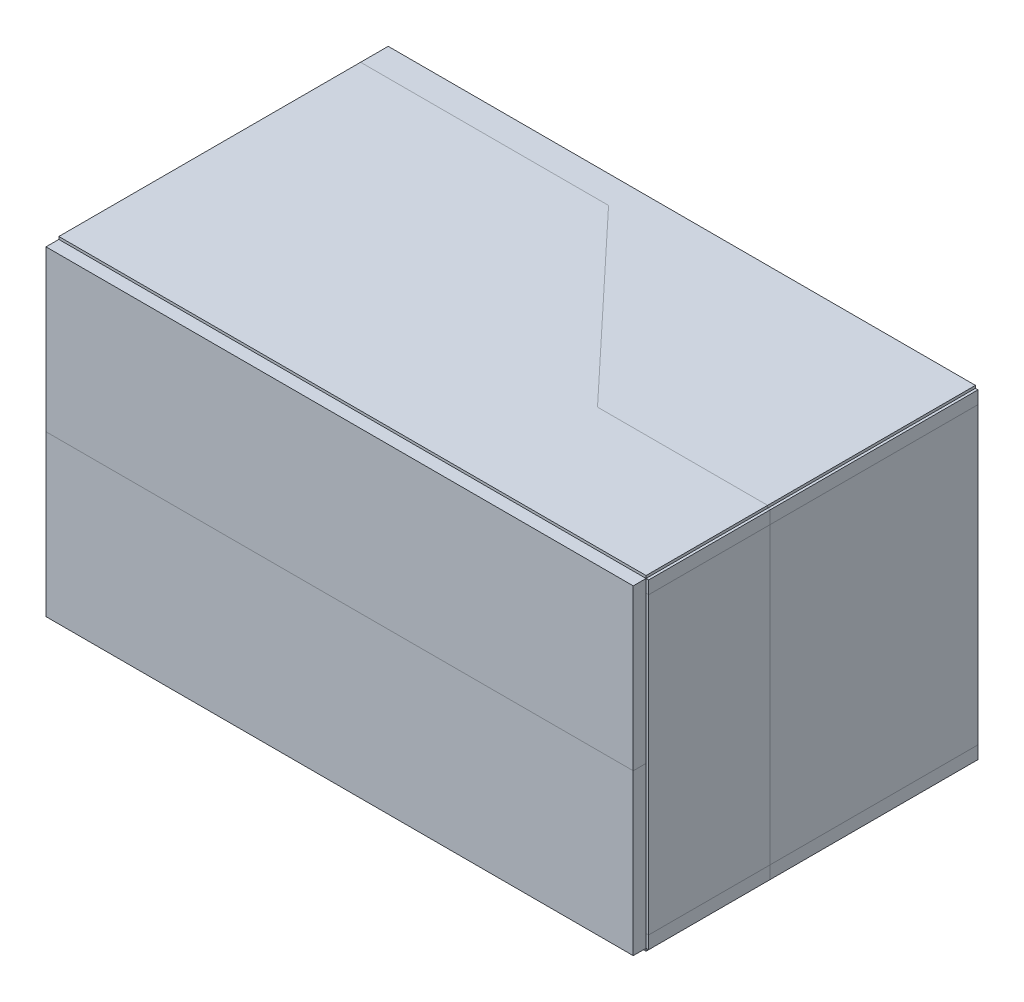
SolidWorks part; units mm, degrees
other "바닥"
other "우측면"
other "정면"
other "좌측면"
other "천장1"
other "천장2"
other "후면"
other "하단인테리어1"
other "상단인테리어1"
other "후면상단작음1"
other "후면하단작음1"
other "후면상단큼1"
other "후면하단큼1"
other "하단인테리어2"
other "상단인테리어2"
other "후면상단작음2"
other "후면하단작음2"
other "세탁건조기1"
other "세탁건조기다이얼1"
other "의자2"
other "의자1"
other "테이블"
other "TV"
other "에어컨"
ref_plane "정면" through (0, 0, 0) normal (0, 0, 1) x (1, 0, 0)
ref_plane "윗면" through (0, 0, 0) normal (0, 1, 0) x (1, 0, 0)
ref_plane "우측면" through (0, 0, 0) normal (1, 0, 0) x (0, 0, -1)
sketch "스케치1" plane through (0, 0, 0) normal (0, 0, 1) x (1, 0, 0)
  line L1 (51, 74.896) -> (280, 74.896)
  line L2 (51, 74.896) -> (51, -50)
  line L3 (51, -50) -> (280, -50)
  line L4 (280, 74.896) -> (280, -50)
extrude "보스-돌출1" add sketch "스케치1" along normal up to surface (7.8606 mm away)
sketch "스케치2" plane through (0, 0, 7.8606) normal (0, 0, 1) x (1, 0, 0)
  line L0 (280, 74.896) -> (280, -50) construction
  line L1 (51, 74.896) -> (280, 74.896)
  line L2 (51, 74.896) -> (51, 69.896)
  line L3 (51, 69.896) -> (280, 69.896)
  line L4 (280, 74.896) -> (280, 69.896)
  dimension "D1" = 5
extrude "컷-돌출1" cut sketch "스케치2" against normal up to surface (7.8606 mm away) contours L1 L3 L2 up to face at (165.5, 12.448, 0)
sketch "스케치4" plane through (0, 0, 7.8606) normal (0, 0, 1) x (1, 0, 0)
  line L0 (280, 69.896) -> (280, -50) construction
  line L1 (51, -50) -> (280, -50)
  line L2 (51, -50) -> (51, -45)
  line L3 (51, -45) -> (280, -45)
  line L4 (280, -50) -> (280, -45)
  line M1 (280, -50) -> (280, 69.896)
  line M3 (51, 69.896) -> (51, -50)
  line M4 (51, -50) -> (280, -50)
  dimension "D1" = 5
extrude "컷-돌출2" cut sketch "스케치4" against normal up to surface (7.8606 mm away) contours L3 M3 M4 M1 up to face at (165.5, 9.948, 0)
sketch "스케치5" plane through (0, 0, 7.8606) normal (0, 0, 1) x (1, 0, 0)
  line L0 (51, -45) -> (280, -45) construction
  line L1 (280, 69.896) -> (275, 69.896)
  line L2 (280, 69.896) -> (280, -45)
  line L3 (280, -45) -> (275, -45)
  line L4 (275, 69.896) -> (275, -45)
  line M1 (51, -45) -> (280, -45)
  line M2 (280, -45) -> (280, 69.896)
  line M3 (280, 69.896) -> (51, 69.896)
  dimension "D1" = 5
extrude "컷-돌출3" cut sketch "스케치5" against normal up to surface (7.8606 mm away) contours L4 M3 M1 M2 up to face at (165.5, 12.448, 0)
sketch "스케치6" plane through (0, 69.896, 0) normal (0, 1, 0) x (1, 0, 0)
  line L1 (51, 0) -> (280, 0)
  line L2 (51, 0) -> (51, -128.4421)
  line L3 (51, -128.4421) -> (280, -128.4421)
  line L4 (280, 0) -> (280, -128.4421)
extrude "보스-돌출3" add sketch "스케치6" along normal blind 5 separate body
sketch "스케치7" plane through (0, 0, 7.8606) normal (0, 0, 1) x (1, 0, 0)
  line L0 (51, -45) -> (275, -45) construction
  line L1 (51, 69.896) -> (56, 69.896)
  line L2 (51, 69.896) -> (51, -45)
  line L3 (51, -45) -> (56, -45)
  line L4 (56, 69.896) -> (56, -45)
  dimension "D1" = 5
extrude "보스-돌출4" add sketch "스케치7" along normal up to surface (120.5815 mm away) separate body up to face at (165.5, 72.396, 128.4421)
sketch "스케치8" plane through (0, -45, 0) normal (0, -1, 0) x (1, 0, 0)
  line L1 (51, 128.4421) -> (280, 128.4421)
  line L2 (51, 128.4421) -> (51, 0)
  line L3 (51, 0) -> (280, 0)
  line L4 (280, 128.4421) -> (280, 0)
extrude "보스-돌출5" add sketch "스케치8" along normal blind 5 separate body
sketch "스케치9" plane through (0, 0, 128.4421) normal (0, 0, 1) x (1, 0, 0)
  line L1 (51, 74.896) -> (280, 74.896)
  line L2 (51, 74.896) -> (51, 12.446)
  line L3 (51, 12.446) -> (280, 12.446)
  line L4 (280, 74.896) -> (280, 12.446)
  dimension "D1" = 62.45
extrude "보스-돌출6" add sketch "스케치9" along normal blind 5 separate body
sketch "스케치10" plane through (0, 0, 128.4421) normal (0, 0, 1) x (1, 0, 0)
  line L1 (51, 12.446) -> (280, 12.446)
  line L2 (51, 12.446) -> (51, -50)
  line L3 (51, -50) -> (280, -50)
  line L4 (280, 12.446) -> (280, -50)
extrude "보스-돌출7" add sketch "스케치10" along normal blind 5 separate body
sketch "스케치11" plane through (275, 0, 0) normal (1, 0, 0) x (0, 0, -1)
  line L1 (0, -45) -> (-128.4421, -45)
  line L2 (0, -45) -> (0, 69.896)
  line L3 (0, 69.896) -> (-128.4421, 69.896)
  line L4 (-128.4421, -45) -> (-128.4421, 69.896)
extrude "보스-돌출8" add sketch "스케치11" along normal blind 5 separate body
sketch "스케치12" plane through (0, -50, 0) normal (0, -1, 0) x (1, 0, 0)
  line L0 (51, 10.7712) -> (147.7059, 10.7712)
  line L1 (51, 128.4421) -> (51, 0) construction
  line L2 (147.7059, 10.7712) -> (213.6585, 81.0356)
  line L3 (213.6585, 81.0356) -> (280, 81.0356)
  line L4 (280, 0) -> (280, 128.4421) construction
  line L5 (51, 10.7712) -> (51, 0)
  line L6 (51, 0) -> (280, 0)
  line L7 (280, 0) -> (280, 81.0356)
extrude "보스-돌출9" add sketch "스케치12" along normal blind 1 separate body
sketch "스케치13" plane through (0, -50, 0) normal (0, -1, 0) x (1, 0, 0)
  line L0 (51, 128.4421) -> (51, 10.7712)
  line L1 (51, 10.7712) -> (147.7059, 10.7712)
  line L2 (147.7059, 10.7712) -> (213.6585, 81.0356)
  line L3 (213.6585, 81.0356) -> (280, 81.0356)
  line L4 (280, 81.0356) -> (280, 128.4421)
  line L5 (280, 128.4421) -> (51, 128.4421)
extrude "보스-돌출10" add sketch "스케치13" along normal blind 1 separate body
sketch "스케치14" plane through (280, 0, 0) normal (1, 0, 0) x (0, 0, -1)
  line L1 (-81.0356, -50) -> (-128.4421, -50)
  line L2 (-81.0356, -50) -> (-81.0356, -45)
  line L3 (-81.0356, -45) -> (-128.4421, -45)
  line L4 (-128.4421, -50) -> (-128.4421, -45)
extrude "보스-돌출11" add sketch "스케치14" along normal blind 1 separate body
sketch "스케치15" plane through (280, 0, 0) normal (1, 0, 0) x (0, 0, -1)
  line L1 (-81.0356, -50) -> (0, -50)
  line L2 (-81.0356, -50) -> (-81.0356, -45)
  line L3 (-81.0356, -45) -> (0, -45)
  line L4 (0, -50) -> (0, -45)
extrude "보스-돌출12" add sketch "스케치15" along normal blind 1 separate body
sketch "스케치16" plane through (280, 0, 0) normal (1, 0, 0) x (0, 0, -1)
  line L0 (-128.4421, 69.896) -> (0, 69.896) construction
  line L1 (-128.4421, -45) -> (-81.0356, -45)
  line L2 (-128.4421, -45) -> (-128.4421, 69.896)
  line L3 (-128.4421, 69.896) -> (-81.0356, 69.896)
  line L4 (-81.0356, -45) -> (-81.0356, 69.896)
extrude "보스-돌출13" add sketch "스케치16" along normal blind 1 separate body
sketch "스케치17" plane through (280, 0, 0) normal (1, 0, 0) x (0, 0, -1)
  line L0 (0, 74.896) -> (0, 69.896) construction
  line L1 (-81.0356, -45) -> (0, -45)
  line L2 (-81.0356, -45) -> (-81.0356, 69.896)
  line L3 (-81.0356, 69.896) -> (0, 69.896)
  line L4 (0, -45) -> (0, 69.896)
  line L5 (-128.4421, 69.896) -> (0, 69.896) construction
extrude "보스-돌출14" add sketch "스케치17" along normal blind 1 separate body
ref_plane "평면1" through (0, 12.446, 0) normal (0, 1, 0) x (1, 0, 0)
mirror "대칭 복사2" about plane through (0, 12.446, 0) normal (0, 1, 0) of bodies 112 113 114 115
other "바디 저장1"
other "바디 저장2"
sketch "스케치18" plane through (0, 0, 7.8606) normal (0, 0, 1) x (1, 0, 0)
  line L1 (56, 69.896) -> (110.75, 69.896)
  line L2 (56, 69.896) -> (56, 29.896)
  line L3 (56, 29.896) -> (110.75, 29.896)
  line L4 (110.75, 69.896) -> (110.75, 29.896)
  dimension "D1" = 54.75
  dimension "D2" = 40
extrude "보스-돌출15" add sketch "스케치18" along normal blind 60.29 separate body
sketch "스케치20" plane through (0, 29.896, 0) normal (0, -1, 0) x (1, 0, 0)
  line L0 (83.375, 68.1506) -> (83.375, 7.8606) construction
  line L1 (56, 68.1506) -> (110.75, 68.1506) construction
  line L2 (56, 7.8606) -> (110.75, 7.8606) construction
  circle A0 centre (83.375, 30.1418) radius 20
  dimension "D1" = 40
extrude "보스-돌출16" add sketch "스케치20" along normal blind 3
sketch "스케치21" plane through (0, 26.896, 0) normal (0, -1, 0) x (1, 0, 0)
  circle A0 centre (83.375, 30.1418) radius 16
  circle A1 centre (83.375, 30.1418) radius 20
  circle A2 centre (83.375, 30.1418) radius 20
  dimension "D1" = 0
  dimension "D2" = 4
extrude "컷-돌출4" cut sketch "스케치21" against normal blind 1 contours A0
sketch "스케치22" plane through (0, 29.896, 0) normal (0, -1, 0) x (1, 0, 0)
  line L0 (83.375, 68.1506) -> (83.375, 7.8606) construction
  line L1 (56, 68.1506) -> (110.75, 68.1506) construction
  line L2 (56, 7.8606) -> (110.75, 7.8606) construction
  circle A0 centre (83.375, 61.1506) radius 3.5
  dimension "D1" = 7
  dimension "D2" = 7
extrude "보스-돌출17" add sketch "스케치22" along normal blind 1 separate body
sketch "스케치23" plane through (0, 29.896, 0) normal (0, -1, 0) x (1, 0, 0)
  line L0 (63.0828, 65.5864) -> (73.9386, 65.5864)
  line L1 (64.0828, 64.5864) -> (72.9386, 64.5864)
  line L2 (61.0828, 61.5864) -> (61.0828, 59.5273)
  line L3 (64.0828, 56.5273) -> (72.9386, 56.5273)
  line L4 (75.9386, 61.5864) -> (75.9386, 59.5273)
  line L5 (76.9386, 62.5864) -> (76.9386, 59.5273)
  line L6 (64.0828, 55.5273) -> (72.9386, 55.5273)
  line L7 (60.0828, 62.5864) -> (60.0828, 59.5273)
  line L8 (60.0828, 65.5864) -> (76.9386, 65.5864) construction
  line L9 (60.0828, 65.5864) -> (60.0828, 59.5273) construction
  line L10 (76.9386, 65.5864) -> (76.9386, 59.5273) construction
  line L11 (61.0828, 64.5864) -> (75.9386, 64.5864) construction
  line L12 (61.0828, 64.5864) -> (61.0828, 59.5273) construction
  line L13 (75.9386, 64.5864) -> (75.9386, 59.5273) construction
  arc A0 (64.0828, 56.5273) -> (61.0828, 59.5273) centre (64.0828, 59.5273) cw
  arc A1 (75.9386, 59.5273) -> (72.9386, 56.5273) centre (72.9386, 59.5273) cw
  arc A2 (76.9386, 59.5273) -> (72.9386, 55.5273) centre (72.9386, 59.5273) cw
  arc A3 (64.0828, 55.5273) -> (60.0828, 59.5273) centre (64.0828, 59.5273) cw
  arc A4 (63.0828, 65.5864) -> (60.0828, 62.5864) centre (63.0828, 62.5864) ccw
  arc A5 (76.9386, 62.5864) -> (73.9386, 65.5864) centre (73.9386, 62.5864) ccw
  arc A6 (64.0828, 64.5864) -> (61.0828, 61.5864) centre (64.0828, 61.5864) ccw
  arc A7 (75.9386, 61.5864) -> (72.9386, 64.5864) centre (72.9386, 61.5864) ccw
  dimension "D1" = 3
  dimension "D2" = 3
  dimension "D4" = 3
  dimension "D5" = 3
  dimension "D6" = 3
  dimension "D7" = 3
  dimension "D3" = 1
extrude "컷-돌출5" cut sketch "스케치23" against normal blind 1
sketch "스케치24" plane through (0, 29.896, 0) normal (0, -1, 0) x (1, 0, 0)
  line L1 (91.1649, 65.5864) -> (107.3673, 65.5864)
  line L2 (91.1649, 65.5864) -> (91.1649, 56.4231)
  line L3 (91.1649, 56.4231) -> (107.3673, 56.4231)
  line L4 (107.3673, 65.5864) -> (107.3673, 56.4231)
extrude "컷-돌출6" cut sketch "스케치24" against normal blind 1
pattern_linear "선형 패턴1" count 4 spacing 54.75 along (1, 0, 0) of bodies 161 163
mirror "대칭 복사3" about plane through (0, 0, 68.1506) normal (0, 0, 1) of bodies 163 161 167 164 168 165 169 166
sketch "스케치25" plane through (56, 0, 0) normal (1, 0, 0) x (0, 0, -1)
  line L1 (-128.4421, -45) -> (-108.4421, -45)
  line L2 (-128.4421, -45) -> (-128.4421, 5)
  line L3 (-128.4421, 5) -> (-108.4421, 5)
  line L4 (-108.4421, -45) -> (-108.4421, 5)
  dimension "D1" = 50
  dimension "D2" = 20
extrude "보스-돌출18" add sketch "스케치25" along normal blind 15 separate body
fillet "필렛1" radius 10 1 edges at (71, -20, 108.4421)
sketch "스케치26" plane through (0, 0, 128.4421) normal (0, 0, 1) x (1, 0, 0)
  line L0 (71, 5) -> (56, 5) construction
  line L1 (57.4417, -43) -> (58.4417, -43)
  line L2 (57.4417, -43) -> (57.4417, 3)
  line L3 (57.4417, 3) -> (58.4417, 3)
  line L4 (58.4417, -43) -> (58.4417, 3)
  line L5 (71, -45) -> (56, -45) construction
  line L6 (59.4417, -43) -> (59.4417, 3)
  line L7 (60.4417, -43) -> (60.4417, 3)
  line L8 (59.4417, -43) -> (60.4417, -43)
  line L9 (59.4417, 3) -> (60.4417, 3)
  line L10 (61.4417, -43) -> (61.4417, 3)
  line L11 (62.4417, -43) -> (62.4417, 3)
  line L12 (61.4417, -43) -> (62.4417, -43)
  line L13 (61.4417, 3) -> (62.4417, 3)
  line L14 (63.4417, -43) -> (63.4417, 3)
  line L15 (64.4417, -43) -> (64.4417, 3)
  line L16 (63.4417, -43) -> (64.4417, -43)
  line L17 (63.4417, 3) -> (64.4417, 3)
  line L18 (65.4417, -43) -> (65.4417, 3)
  line L19 (66.4417, -43) -> (66.4417, 3)
  line L20 (65.4417, -43) -> (66.4417, -43)
  line L21 (65.4417, 3) -> (66.4417, 3)
  line L22 (67.4417, -43) -> (67.4417, 3)
  line L23 (68.4417, -43) -> (68.4417, 3)
  line L24 (67.4417, -43) -> (68.4417, -43)
  line L25 (67.4417, 3) -> (68.4417, 3)
  dimension "D1" = 1
  dimension "D2" = 2
  dimension "D3" = 2
  dimension "D4" = 6
extrude "컷-돌출7" cut sketch "스케치26" against normal blind 10
sketch "스케치27" plane through (56, 0, 0) normal (1, 0, 0) x (0, 0, -1)
  line L0 (-128.4421, -45) -> (-7.8606, -45) construction
  line L1 (-103.4421, -45) -> (-68.4421, -45)
  line L2 (-103.4421, -45) -> (-103.4421, 17.2222)
  line L3 (-103.4421, 17.2222) -> (-68.4421, 17.2222)
  line L4 (-68.4421, -45) -> (-68.4421, 17.2222)
  line L5 (-108.4421, -45) -> (-108.4421, 5) construction
  dimension "D1" = 35
  dimension "D2" = 62.2222
  dimension "D3" = 5
extrude "보스-돌출19" add sketch "스케치27" along normal blind 3 separate body
sketch "스케치28" plane through (59, 0, 0) normal (1, 0, 0) x (0, 0, -1)
  line L0 (-101.4421, 15.2222) -> (-101.4421, -43)
  line L1 (-101.4421, -43) -> (-70.4421, -43)
  line L2 (-70.4421, -43) -> (-70.4421, 15.2222)
  line L3 (-70.4421, 15.2222) -> (-101.4421, 15.2222)
  line L4 (-103.4421, 17.2222) -> (-103.4421, -45)
  line L5 (-103.4421, -45) -> (-68.4421, -45)
  line L6 (-68.4421, -45) -> (-68.4421, 17.2222)
  line L7 (-68.4421, 17.2222) -> (-103.4421, 17.2222)
  line L8 (-103.4421, 17.2222) -> (-103.4421, -45)
  line L9 (-103.4421, -45) -> (-68.4421, -45)
  line L10 (-68.4421, -45) -> (-68.4421, 17.2222)
  line L11 (-68.4421, 17.2222) -> (-103.4421, 17.2222)
  dimension "D1" = 0
  dimension "D2" = 2
extrude "컷-돌출8" cut sketch "스케치28" against normal blind 1.5 contours L2 L3 L0 L1
sketch "스케치29" plane through (0, 0, 7.8606) normal (0, 0, 1) x (1, 0, 0)
  line L1 (149.8142, -18.5336) -> (154.8142, -18.5336)
  line L2 (149.8142, -18.5336) -> (149.8142, -23.5336)
  line L3 (149.8142, -23.5336) -> (154.8142, -23.5336)
  line L4 (154.8142, -18.5336) -> (154.8142, -23.5336)
  dimension "D1" = 5
  dimension "D2" = 5
extrude "보스-돌출20" add sketch "스케치29" along normal blind 37.5 separate body
sketch "스케치30" plane through (0, 0, 45.3606) normal (0, 0, 1) x (1, 0, 0)
  line L0 (152.3142, -18.5336) -> (152.3142, -23.5336) construction
  line L1 (154.8142, -18.5336) -> (149.8142, -18.5336) construction
  line L2 (149.8142, -23.5336) -> (154.8142, -23.5336) construction
  line L3 (51, -45) -> (275, -45) construction
  line L4 (128.0078, 2.9329) -> (176.6207, 2.9329)
  line L5 (128.0078, 2.9329) -> (128.0078, -45)
  line L6 (128.0078, -45) -> (176.6207, -45)
  line L7 (176.6207, 2.9329) -> (176.6207, -45)
  line L8 (128.0078, 2.9329) -> (176.6207, -45) construction
  line L9 (128.0078, -45) -> (176.6207, 2.9329) construction
  point P6 (152.3142, -21.0336)
extrude "보스-돌출21" add sketch "스케치30" along normal blind 5
sketch "스케치31" plane through (0, 0, 7.8606) normal (0, 0, 1) x (1, 0, 0)
  line L0 (119.6722, -13.1518) -> (124.6722, -13.1518)
  line L5 (104.6722, -13.1518) -> (109.6722, -13.1518)
  line L6 (104.6722, -13.1518) -> (104.6722, -18.1518)
  line L7 (104.6722, -18.1518) -> (109.6722, -18.1518)
  line L8 (109.6722, -13.1518) -> (109.6722, -18.1518)
  line L9 (119.6722, -13.1518) -> (119.6722, -18.1518)
  line L10 (124.6722, -13.1518) -> (124.6722, -18.1518)
  line L11 (119.6722, -18.1518) -> (124.6722, -18.1518)
  line L12 (119.6722, -28.1518) -> (124.6722, -28.1518)
  line L13 (119.6722, -28.1518) -> (119.6722, -33.1518)
  line L14 (124.6722, -28.1518) -> (124.6722, -33.1518)
  line L15 (119.6722, -33.1518) -> (124.6722, -33.1518)
  line L16 (104.6722, -28.1518) -> (109.6722, -28.1518)
  line L17 (104.6722, -28.1518) -> (104.6722, -33.1518)
  line L18 (109.6722, -28.1518) -> (109.6722, -33.1518)
  line L19 (104.6722, -33.1518) -> (109.6722, -33.1518)
  dimension "D1" = 2
  dimension "D2" = 2
  dimension "D3" = 5
  dimension "D4" = 5
extrude "보스-돌출22" add sketch "스케치31" along normal blind 26 separate body
sketch "스케치32" plane through (0, 0, 33.8606) normal (0, 0, 1) x (1, 0, 0)
  line L1 (104.6722, -13.1518) -> (124.6722, -13.1518)
  line L2 (104.6722, -13.1518) -> (104.6722, -33.1518)
  line L3 (104.6722, -33.1518) -> (124.6722, -33.1518)
  line L4 (124.6722, -13.1518) -> (124.6722, -33.1518)
extrude "보스-돌출23" add sketch "스케치32" along normal blind 42
sketch "스케치33" plane through (0, 0, 75.8606) normal (0, 0, 1) x (1, 0, 0)
  line L0 (124.6722, -13.1518) -> (104.6722, -13.1518) construction
  line L1 (124.6722, -33.1518) -> (108.7481, -33.1518)
  line L2 (124.6722, -33.1518) -> (124.6722, -13.1518)
  line L3 (124.6722, -13.1518) -> (108.7481, -13.1518)
  line L4 (108.7481, -33.1518) -> (108.7481, -13.1518)
extrude "컷-돌출9" cut sketch "스케치33" against normal blind 37
ref_plane "평면2" through (152.3128, 0, 0) normal (-1, 0, 0) x (0, 0, 1)
mirror "대칭 복사4" about plane through (152.3128, 0, 0) normal (-1, 0, 0)
